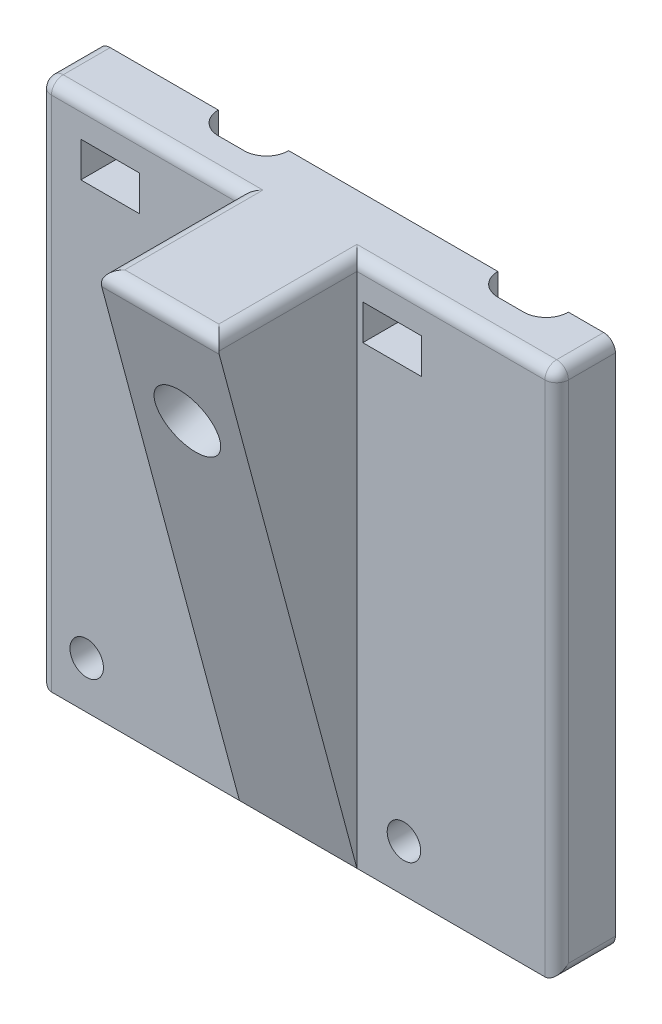
SolidWorks part; units mm, degrees
ref_plane "Front Plane" through (0, 0, 0) normal (0, 0, 1) x (1, 0, 0)
ref_plane "Top Plane" through (0, 0, 0) normal (0, 1, 0) x (1, 0, 0)
ref_plane "Right Plane" through (0, 0, 0) normal (1, 0, 0) x (0, 0, -1)
sketch "Sketch1" plane through (0, 0, 0) normal (0, 0, 1) x (1, 0, 0)
  line L1 (-22, 22.5) -> (22, 22.5)
  line L2 (-22, 22.5) -> (-22, -22.5)
  line L3 (-22, -22.5) -> (22, -22.5)
  line L4 (22, 22.5) -> (22, -22.5)
  line L5 (-22, 22.5) -> (22, -22.5) construction
  line L6 (-22, -22.5) -> (22, 22.5) construction
  point P0 (0, 0)
  dimension "D1" = 44
  dimension "D2" = 45
extrude "Base" add sketch "Sketch1" along normal blind 5
sketch "Sketch2" plane through (0, 22.5, 0) normal (0, 1, 0) x (1, 0, 0)
  line L0 (22, 0) -> (-22, 0) construction
  line L1 (12, 0) -> (18, 0)
  line L2 (12, 0) -> (12, -5) construction
  line L3 (22, -5) -> (-22, -5) construction
  line L5 (13.9, -1.9) -> (16.1, -1.9)
  line L6 (3.1, 0) -> (3.1, -5) construction
  line L7 (-7.7, -1.9) -> (-9.9, -1.9)
  line L8 (-5.8, 0) -> (-11.8, 0)
  arc A1 (12, 0) -> (13.9, -1.9) centre (13.9, 0) ccw
  arc A2 (16.1, -1.9) -> (18, 0) centre (16.1, 0) ccw
  arc A3 (-5.8, 0) -> (-7.7, -1.9) centre (-7.7, 0) cw
  arc A4 (-9.9, -1.9) -> (-11.8, 0) centre (-9.9, 0) cw
  point P5 (15, 0)
  dimension "D1" = 15
  dimension "D2" = 6
  dimension "D3" = 1.9
  dimension "D4" = 11.9
extrude "Wire Grooves" cut sketch "Sketch2" against normal through all
sketch "Sketch4" plane through (22, 0, 0) normal (1, 0, 0) x (0, 0, -1)
  line L0 (-5, -22.5) -> (-5, 22.5)
  line L1 (-5, -22.5) -> (-17.0577, 22.5)
  line L2 (-17.0577, 22.5) -> (-5, 22.5)
  dimension "D1" = 15
extrude "Slanted Screw Platform" add sketch "Sketch4" against normal mid plane 10 from surface at -22 starting at plane "Right Plane"
sketch "Sketch5" plane through (0, -2.7572, 10.2901) normal (0, -0.2588, 0.9659) x (1, 0, 0)
  line L0 (0, 0) -> (0, 26.1482) construction
  line L1 (-5, 26.1482) -> (5, 26.1482) construction
  circle A0 centre (0, 16) radius 2.75
  dimension "D1" = 5.5
  dimension "D2" = 16
extrude "Mounting Hole Screw Insertion" cut sketch "Sketch5" against normal through all
sketch "Sketch6" plane through (0, 0, 5) normal (0, 0, 1) x (1, 0, 0)
  line L0 (0, 22.5) -> (0, -22.5) construction
  line L1 (-5, 22.5) -> (5, 22.5) construction
  line L2 (-5, -22.5) -> (5, -22.5) construction
  line L4 (-18.5, 19.5) -> (-13.5, 19.5)
  line L5 (-18.5, 19.5) -> (-18.5, 16.5)
  line L6 (-18.5, 16.5) -> (-13.5, 16.5)
  line L7 (-13.5, 19.5) -> (-13.5, 16.5)
  line L8 (-5, 22.5) -> (-22, 22.5) construction
  line L9 (-4, 22.5) -> (-4, -22.5) construction
  line L11 (10.5, 16.5) -> (5.5, 16.5)
  line L12 (5.5, 19.5) -> (5.5, 16.5)
  line L13 (10.5, 19.5) -> (5.5, 19.5)
  line L14 (10.5, 19.5) -> (10.5, 16.5)
  point P16 (-16, 16.5)
  dimension "D1" = 5
  dimension "D2" = 3
  dimension "D3" = 3
  dimension "D4" = 16
  dimension "D5" = 4
extrude "Zip Tie Slots" cut sketch "Sketch6" against normal through all
sketch "Sketch7" plane through (0, 0, 5) normal (0, 0, 1) x (1, 0, 0)
  line L0 (-22, 22.5) -> (-22, -22.5) construction
  line L1 (-22, -22.5) -> (-5, -22.5) construction
  line L2 (-4.5, 22.5) -> (-4.5, -22.5) construction
  line L5 (-5, 22.5) -> (5, 22.5) construction
  line L6 (-5, -22.5) -> (5, -22.5) construction
  circle A0 centre (-18, -18.5) radius 1.425
  circle A2 centre (9, -18.5) radius 1.425
  point P8 (0, 0)
  point P11 (0, 0)
  dimension "D1" = 2.85
  dimension "D2" = 4
  dimension "D3" = 4
  dimension "D4" = 4.5
extrude "Mount Clamping Holes" cut sketch "Sketch7" against normal through all
fillet "Edge Fillets" radius 1 11 edges at (22, 0, 5) (-5, 22.5, 11.0289) (0, 22.5, 17.0577) (5, 22.5, 11.0289) (13.5, 22.5, 5) (-22, 0, 5) (-13.5, 22.5, 5) (22, -22.5, 2.5) (-22, -22.5, 2.5) (22, 22.5, 2.5) (-22, 22.5, 2.5)
